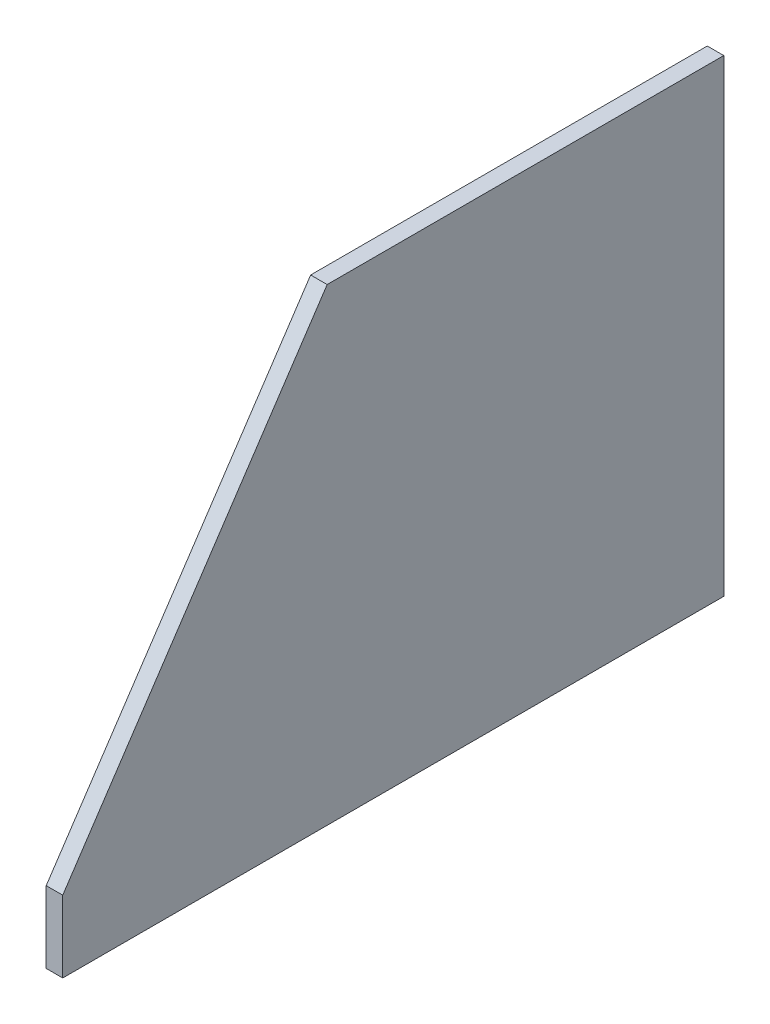
SolidWorks part; units mm, degrees
ref_plane "Plan de face" through (0, 0, 0) normal (0, 0, 1) x (1, 0, 0)
ref_plane "Plan de dessus" through (0, 0, 0) normal (0, 1, 0) x (1, 0, 0)
ref_plane "Plan de droite" through (0, 0, 0) normal (1, 0, 0) x (0, 0, -1)
sketch "Esquisse2" plane through (0, 0, 0) normal (1, 0, 0) x (0, 0, -1)
  line L0 (0, 0) -> (-254, 0)
  line L1 (-254, 0) -> (-254, -27.559)
  line L2 (-254, -27.559) -> (0, -27.559)
  line L3 (0, -27.559) -> (0, 0)
  line L4 (-254, 0) -> (-152.4, 152.4)
  line L5 (-152.4, 152.4) -> (0, 152.4)
  line L6 (0, 152.4) -> (0, 0)
  dimension "D1" = 27.559
  dimension "D2" = 152.4
  dimension "D3" = 254
  dimension "D4" = 152.4
  dimension "D5" = 0
extrude "Boss.-Extru.1" add sketch "Esquisse2" along normal blind 6.35
